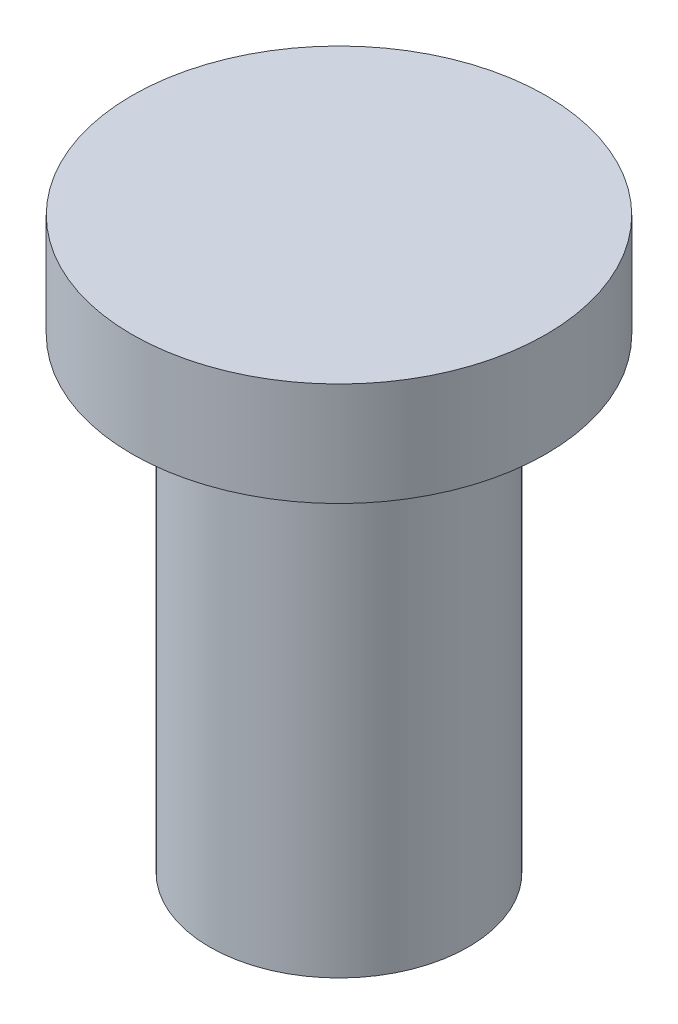
SolidWorks part; units mm, degrees
ref_plane "Front Plane" through (0, 0, 0) normal (0, 0, 1) x (1, 0, 0)
ref_plane "Top Plane" through (0, 0, 0) normal (0, 1, 0) x (1, 0, 0)
ref_plane "Right Plane" through (0, 0, 0) normal (1, 0, 0) x (0, 0, -1)
sketch "Sketch3" plane through (0, 0, 0) normal (0, 1, 0) x (1, 0, 0)
  circle A0 centre (0, 0) radius 1.25
extrude "Boss-Extrude1" add sketch "Sketch3" along normal blind 4.5
sketch "Sketch4" plane through (0, 4.5, 0) normal (0, 1, 0) x (1, 0, 0)
  circle A0 centre (0, 0) radius 2
extrude "Boss-Extrude2" add sketch "Sketch4" along normal blind 1
